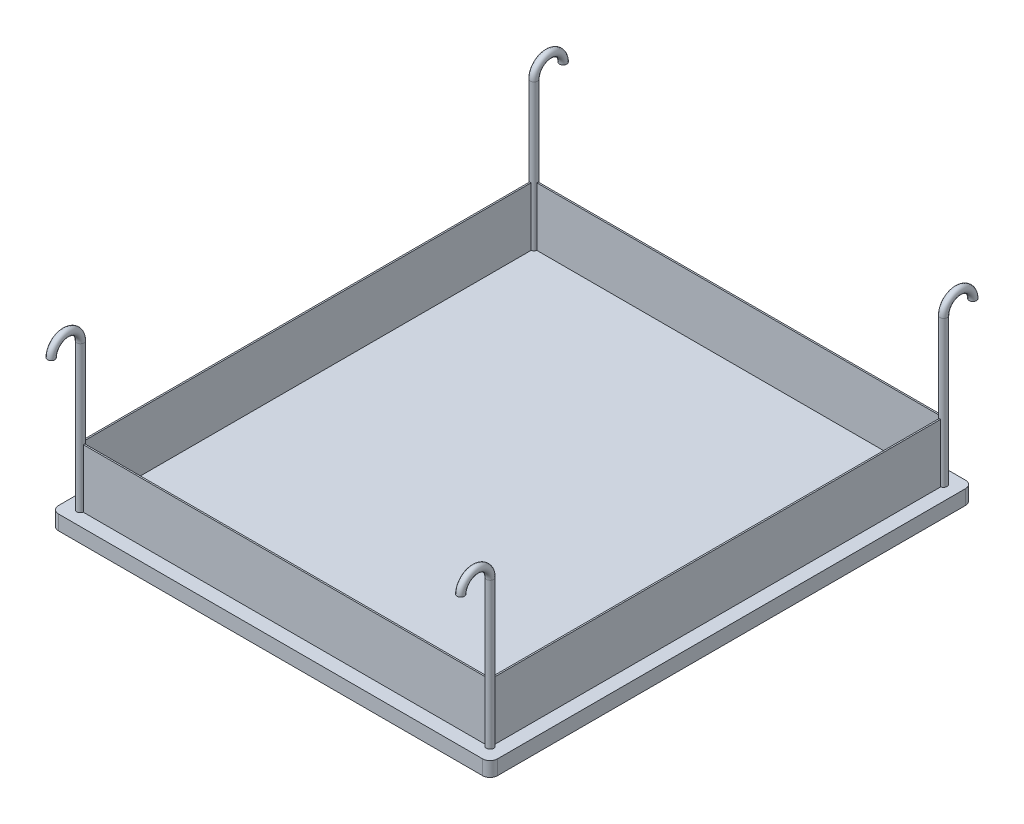
SolidWorks part; units mm, degrees
ref_plane "Front Plane" through (0, 0, 0) normal (0, 0, 1) x (1, 0, 0)
ref_plane "Top Plane" through (0, 0, 0) normal (0, 1, 0) x (1, 0, 0)
ref_plane "Right Plane" through (0, 0, 0) normal (1, 0, 0) x (0, 0, -1)
sketch "Sketch1" plane through (0, 0, 0) normal (0, 1, 0) x (1, 0, 0)
  line L1 (-150, 0) -> (150, 0)
  line L2 (-150, 0) -> (-150, -165)
  line L3 (-150, -165) -> (150, -165)
  line L4 (150, 0) -> (150, -165)
  point P4 (0, 0)
  dimension "D1" = 165
  dimension "D2" = 300
extrude "Boss-Extrude1" add sketch "Sketch1" along normal blind 10
sketch "Sketch2" plane through (0, 10, 0) normal (0, 1, 0) x (1, 0, 0)
  line L0 (-140, -165) -> (-140, -155) construction
  line L1 (-150, -165) -> (150, -165) construction
  line L2 (-140, -155) -> (-150, -155) construction
  line L3 (-150, 0) -> (-150, -165) construction
  line L4 (140, -165) -> (140, -155) construction
  line L5 (140, -155) -> (150, -155) construction
  line L6 (150, -165) -> (150, 0) construction
  circle A0 centre (-140, -155) radius 2.5
  circle A1 centre (140, -155) radius 2.5
  point P14 (100.9971, -125.9971)
  point P15 (-122.8066, -147.8066)
  point P17 (0, 0)
  dimension "D1" = 5
  dimension "D2" = 10
sketch "Sketch3" plane through (0, 0, 0) normal (1, 0, 0) x (0, 0, -1)
  line L0 (-155, 10) -> (-155, 110)
  line L1 (-152.5, 10) -> (-157.5, 10) construction
  line L2 (-165, 10) -> (-165, 110) construction
  line L3 (-165, 110) -> (-155, 110) construction
  arc A0 (-155, 110) -> (-175, 110) centre (-165, 110) ccw
  point P7 (-190, 103.2955)
  point P8 (-170, 110)
  dimension "D1" = 100
sweep "Sweep1" add profiles "Sketch2" path "Sketch3"
fillet "Fillet1" radius 5 2 edges at (-150, 5, 165) (150, 5, 165)
sketch "Sketch4" plane through (0, 10, 0) normal (0, 1, 0) x (1, 0, 0)
  line L0 (-140, 0) -> (-140, -155)
  line L1 (150, 0) -> (-150, 0) construction
  line L2 (-140, -155) -> (140, -155)
  line L3 (140, -155) -> (140, 0)
  line L4 (140, -22.0762) -> (150, -22.0762) construction
  line L5 (150, -160) -> (150, 0) construction
  line L6 (-14.3597, -155) -> (-14.3597, -165) construction
  line L7 (-145, -165) -> (145, -165) construction
  line L8 (-140, -108.6663) -> (-150, -108.6663) construction
  line L9 (-150, 0) -> (-150, -160) construction
  point P18 (-135, -160)
extrude "Extrude-Thin1" add sketch "Sketch4" along normal blind 40 thin thin type mid plane wall 1
mirror "Mirror1" about plane through (-150, 10, 0) normal (0, 0, 1) of "Extrude-Thin1", "Fillet1", "Sweep1", "Boss-Extrude1"
